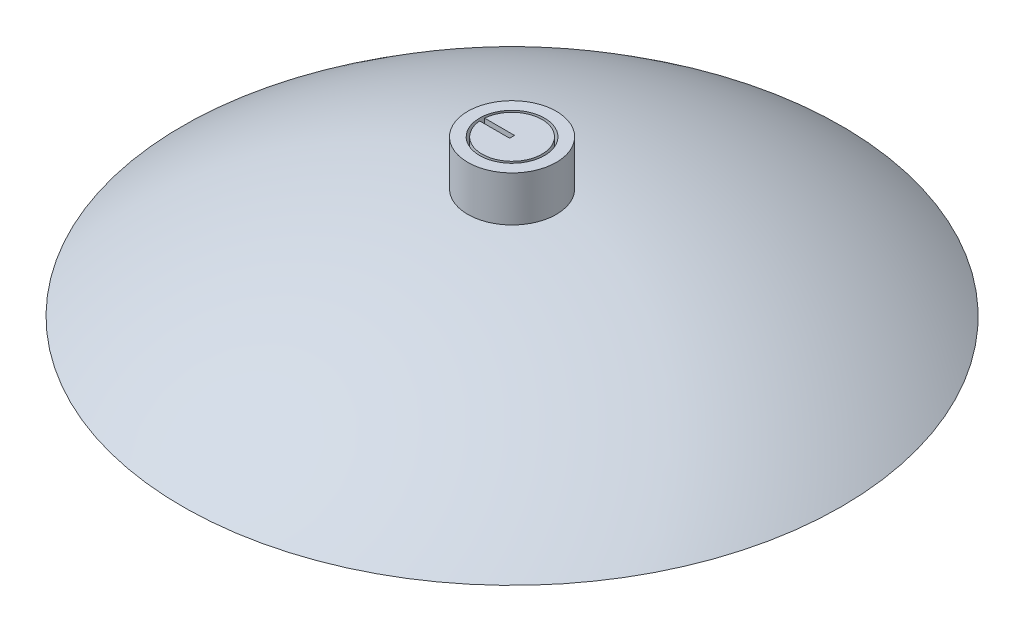
SolidWorks part; units mm, degrees
material "AISI 1020"
ref_plane "Front Plane" through (0, 0, 0) normal (0, 0, 1) x (1, 0, 0)
ref_plane "Top Plane" through (0, 0, 0) normal (0, 1, 0) x (1, 0, 0)
ref_plane "Right Plane" through (0, 0, 0) normal (1, 0, 0) x (0, 0, -1)
sketch "Sketch1" plane through (0, 0, 0) normal (0, 0, 1) x (1, 0, 0)
  line L0 (0, 0) -> (0, -84594.022) construction
  line L1 (212.725, 0) -> (191.135, 0)
  line L2 (0, 0) -> (191.135, 0) construction
  line L3 (0, 72.39) -> (212.725, 72.39) construction
  line L4 (212.725, 72.39) -> (212.725, 0) construction
  line L5 (0, 72.39) -> (0, 50.8)
  arc A0 (212.725, 0) -> (0, 72.39) centre (0, -276.3615) ccw
  arc A1 (191.135, 0) -> (0, 50.8) centre (9.6625, -297.8176) ccw
  dimension "D1" = 212.725
  dimension "D2" = 72.39
  dimension "D3" = 21.59
  dimension "D4" = 21.59
revolve "Revolve1" add sketch "Sketch1" angle 360 about L0
ref_plane "Plane1" through (0, 100.33, 0) normal (0, 1, 0) x (1, 0, 0)
sketch "Sketch2" plane through (0, 100.33, 0) normal (0, 1, 0) x (1, 0, 0)
  circle A0 centre (0, 0) radius 28.575
  dimension "D1" = 57.15
extrude "Boss-Extrude1" add sketch "Sketch2" against normal up to surface (29.1126 mm away)
sketch "Sketch3" plane through (0, 100.33, 0) normal (0, 1, 0) x (1, 0, 0)
  circle A0 centre (0, 0) radius 19.3675
  circle A1 centre (0, 0) radius 20.955
  dimension "D1" = 38.735
  dimension "D2" = 1.5875
extrude "Cut-Extrude1" cut sketch "Sketch3" against normal up to surface (28.4782 mm away)
sketch "Sketch4" plane through (0, 100.33, 0) normal (0, 1, 0) x (1, 0, 0)
  line L0 (-19.3023, 1.5875) -> (0, 1.5875)
  line L1 (0, 1.5875) -> (0, -1.5875)
  line L2 (0, -1.5875) -> (-19.3023, -1.5875)
  circle A0 centre (0, 0) radius 19.3675 construction
  arc A1 (-19.3023, -1.5875) -> (-19.3023, 1.5875) centre (-17.7148, 0) cw
  point P4 (0, 0)
  point P8 (0, 0)
  dimension "D2" = 2.2451
  dimension "D1" = 3.175
extrude "Cut-Extrude2" cut sketch "Sketch4" against normal up to surface (28.4782 mm away)
ref_plane "Plane2" through (0, 51.308, 0) normal (0, 1, 0) x (1, 0, 0)
sketch "Sketch6" plane through (0, 51.308, 0) normal (0, 1, 0) x (1, 0, 0)
  circle A0 centre (0, 0) radius 6.985
  dimension "D1" = 13.97
extrude "Boss-Extrude4" add sketch "Sketch6" against normal blind 19.05
sketch "Sketch7" plane through (0, 32.258, 0) normal (0, -1, 0) x (1, 0, 0)
  circle A0 centre (0, 0) radius 5.715
  circle A1 centre (0, 0) radius 6.985 construction
  dimension "D1" = 1.27
extrude "Cut-Extrude3" cut sketch "Sketch7" against normal blind 16.51
